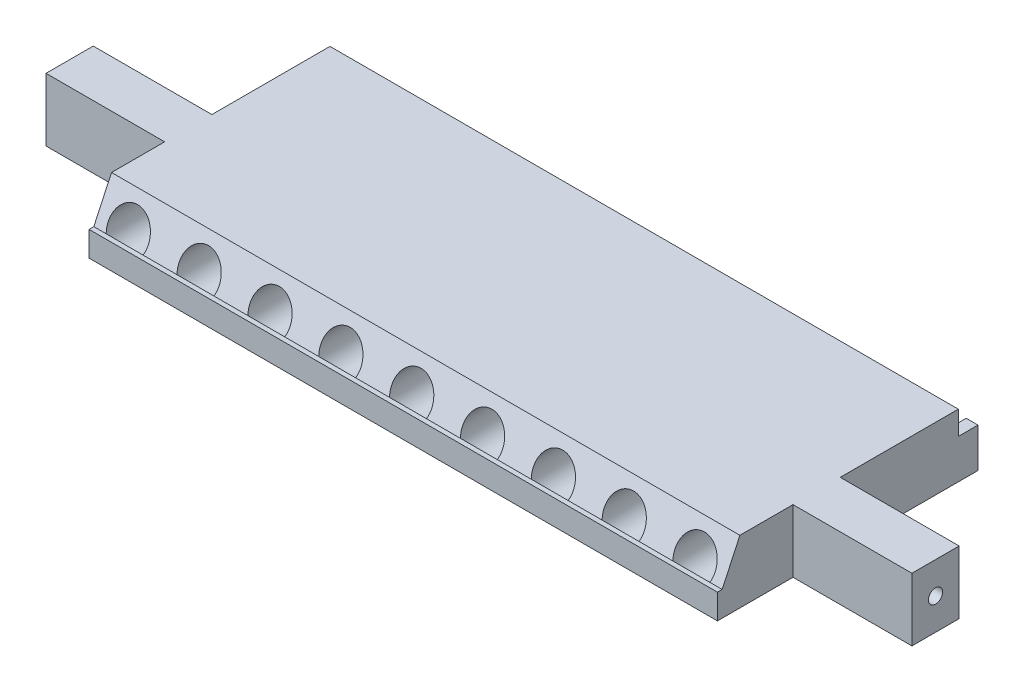
SolidWorks part; units mm, degrees
ref_plane "Спереди" through (0, 0, 0) normal (0, 0, 1) x (1, 0, 0)
ref_plane "Сверху" through (0, 0, 0) normal (0, 1, 0) x (1, 0, 0)
ref_plane "Справа" through (0, 0, 0) normal (1, 0, 0) x (0, 0, -1)
sketch "Эскиз1" plane through (0, 0, 0) normal (0, 0, 1) x (1, 0, 0)
  line L1 (0, 0) -> (220, 0)
  line L2 (0, 0) -> (0, 16)
  line L3 (0, 16) -> (220, 16)
  line L4 (220, 0) -> (220, 16)
  circle A0 centre (37.97, 8.3394) radius 5.1
  circle A9 centre (55.97, 8.3394) radius 5.1
  circle A10 centre (73.97, 8.3394) radius 5.1
  circle A11 centre (91.97, 8.3394) radius 5.1
  circle A12 centre (109.97, 8.3394) radius 5.1
  circle A13 centre (127.97, 8.3394) radius 5.1
  circle A14 centre (145.97, 8.3394) radius 5.1
  circle A15 centre (163.97, 8.3394) radius 5.1
  circle A16 centre (181.97, 8.3394) radius 5.1
  dimension "D3" = 10.2
  dimension "D6" = 38.03
  dimension "D7" = 7.8
  dimension "D1" = 16
  dimension "D2" = 220
  dimension "D4" = 37.97
  dimension "D5" = 9
extrude "Бобышка-Вытянуть1" add sketch "Эскиз1" along normal blind 65
sketch "Эскиз2" plane through (0, 16, 0) normal (0, 1, 0) x (1, 0, 0)
  line L0 (220, -65) -> (220, 0) construction
  line L1 (0, 0) -> (220, 0)
  line L2 (0, 0) -> (0, -5)
  line L3 (0, -5) -> (220, -5)
  line L4 (220, 0) -> (220, -5)
  dimension "D1" = 5
extrude "Вырез-Вытянуть1" cut sketch "Эскиз2" against normal blind 6
sketch "Эскиз3" plane through (0, 16, 0) normal (0, 1, 0) x (1, 0, 0)
  line L0 (220, -65) -> (0, -65) construction
  line L1 (0, 0) -> (30.1479, 0)
  line L2 (0, 0) -> (0, -35)
  line L3 (0, -35) -> (30.1479, -35)
  line L4 (30.1479, 0) -> (30.1479, -35)
  line L5 (0, -65) -> (30.1479, -65)
  line L6 (0, -65) -> (0, -47)
  line L7 (0, -47) -> (30.1479, -47)
  line L8 (30.1479, -65) -> (30.1479, -47)
  line L9 (186.7921, -5) -> (186.7921, 0) construction
  line L10 (220, 0) -> (189.7921, 0)
  line L11 (220, 0) -> (220, -35)
  line L12 (220, -35) -> (189.7921, -35)
  line L13 (189.7921, 0) -> (189.7921, -35)
  line L14 (220, -65) -> (189.7921, -65)
  line L15 (220, -65) -> (220, -47)
  line L16 (220, -47) -> (189.7921, -47)
  line L17 (189.7921, -65) -> (189.7921, -47)
  line L18 (33.1479, 0) -> (33.1479, -5) construction
  dimension "D1" = 12
  dimension "D2" = 12
  dimension "D3" = 18
  dimension "D4" = 18
  dimension "D5" = 3
  dimension "D6" = 3
  dimension "D7" = 3
  dimension "D8" = 3
extrude "Вырез-Вытянуть2" cut sketch "Эскиз3" against normal through all
sketch "Эскиз4" plane through (0, 0, 0) normal (-1, 0, 0) x (0, 0, 1)
  line L3 (47, 0) -> (35, 0) construction
  line L4 (35, 0) -> (35, 16) construction
  circle A0 centre (41, 8) radius 1.8
  dimension "D1" = 3.6
  dimension "D2" = 6
  dimension "D3" = 8
extrude "Вырез-Вытянуть3" cut sketch "Эскиз4" against normal blind 10
sketch "Эскиз5" plane through (220, 0, 0) normal (1, 0, 0) x (0, 0, -1)
  line L0 (-47, 16) -> (-35, 16) construction
  line L1 (-47, 0) -> (-47, 16) construction
  circle A0 centre (-41, 8) radius 1.8
  dimension "D1" = 3.6
  dimension "D2" = 8
  dimension "D3" = 6
extrude "Вырез-Вытянуть4" cut sketch "Эскиз5" against normal blind 10
sketch "Эскиз8" plane through (189.7921, 0, 0) normal (1, 0, 0) x (0, 0, -1)
  line L0 (-65, 6.3318) -> (-60.5004, 16)
  line L1 (-65, 0) -> (-65, 16) construction
  line L2 (-47, 16) -> (-65, 16) construction
  line L3 (-60.5004, 16) -> (-65, 16)
  line L4 (-65, 16) -> (-65, 6.3318)
  point P8 (-65, 9.1606)
  point P9 (-65, 6.3318)
extrude "Вырез-Вытянуть7" cut sketch "Эскиз8" against normal through all
sketch "Эскиз9" plane through (0, 0, 65) normal (0, 0, 1) x (1, 0, 0)
  line L1 (30.1479, 0) -> (189.7921, 0)
  line L2 (30.1479, 0) -> (30.1479, 6.3318)
  line L3 (30.1479, 6.3318) -> (189.7921, 6.3318)
  line L4 (189.7921, 0) -> (189.7921, 6.3318)
extrude "Бобышка-Вытянуть2" add sketch "Эскиз9" along normal blind 1.2
